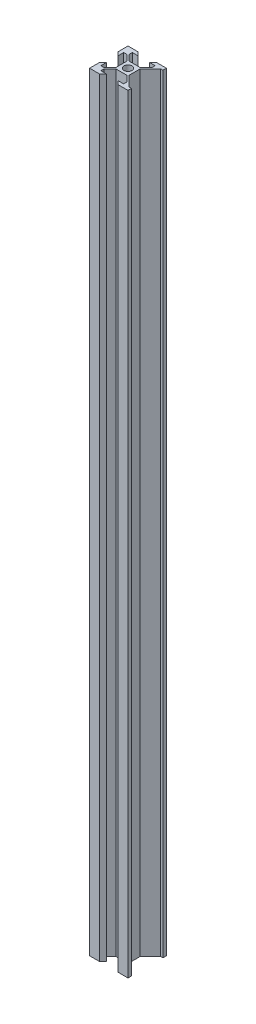
SolidWorks part; units mm, degrees
ref_plane "前视基准面" through (0, 0, 0) normal (0, 0, 1) x (1, 0, 0)
ref_plane "上视基准面" through (0, 0, 0) normal (0, 1, 0) x (1, 0, 0)
ref_plane "右视基准面" through (0, 0, 0) normal (1, 0, 0) x (0, 0, -1)
sketch "草图1" plane through (0, 0, 0) normal (0, 1, 0) x (1, 0, 0)
  line L0 (-25.721, 0) -> (73.7722, 0)
  line L1 (0, 21.255) -> (0, -16.6235)
  line L2 (-10, 21.255) -> (-10, -16.6235)
  line L3 (-25.721, 10) -> (73.7722, 10)
  line L4 (-4.9, 10) -> (-3.1, 8.2)
  line L5 (-3.1, 8.2) -> (-5.9236, 8.2)
  line L6 (-5.9236, 8.2) -> (-5.9236, 6.56)
  line L7 (-5.9236, 6.56) -> (-2.84, 3.4764)
  line L8 (-2.84, 3.4764) -> (2.84, 3.4764)
  line L9 (-10, 10) -> (0, 0) construction
  line L10 (5.9236, 6.56) -> (2.84, 3.4764)
  line L11 (5.9236, 8.2) -> (5.9236, 6.56)
  line L12 (3.1, 8.2) -> (5.9236, 8.2)
  line L13 (4.9, 10) -> (3.1, 8.2)
  line L14 (-10, -4.9) -> (-8.2, -3.1)
  line L15 (-8.2, -3.1) -> (-8.2, -5.9236)
  line L16 (-8.2, -5.9236) -> (-6.56, -5.9236)
  line L17 (-6.56, -5.9236) -> (-3.4764, -2.84)
  line L18 (-3.4764, 2.84) -> (-3.4764, -2.84)
  line L19 (-6.56, 5.9236) -> (-3.4764, 2.84)
  line L20 (-8.2, 5.9236) -> (-6.56, 5.9236)
  line L21 (-8.2, 3.1) -> (-8.2, 5.9236)
  line L22 (-10, 4.9) -> (-8.2, 3.1)
  line L23 (-25.721, -10) -> (73.7722, -10)
  line L24 (4.9, -10) -> (3.1, -8.2)
  line L25 (3.1, -8.2) -> (5.9236, -8.2)
  line L26 (5.9236, -8.2) -> (5.9236, -6.56)
  line L27 (5.9236, -6.56) -> (2.84, -3.4764)
  line L28 (-2.84, -3.4764) -> (2.84, -3.4764)
  line L29 (-5.9236, -6.56) -> (-2.84, -3.4764)
  line L30 (-5.9236, -8.2) -> (-5.9236, -6.56)
  line L31 (-3.1, -8.2) -> (-5.9236, -8.2)
  line L32 (-4.9, -10) -> (-3.1, -8.2)
  line L33 (50, 21.255) -> (50, -16.6235)
  line L34 (20, 21.255) -> (20, -16.6235)
  line L35 (10, 4.9) -> (8.2, 3.1)
  line L36 (8.2, 3.1) -> (8.2, 5.9236)
  line L37 (8.2, 5.9236) -> (6.56, 5.9236)
  line L38 (6.56, 5.9236) -> (3.4764, 2.84)
  line L39 (3.4764, 2.84) -> (3.4764, -2.84)
  line L40 (6.56, -5.9236) -> (3.4764, -2.84)
  line L41 (8.2, -5.9236) -> (6.56, -5.9236)
  line L42 (8.2, -3.1) -> (8.2, -5.9236)
  line L43 (10, -4.9) -> (8.2, -3.1)
  line L44 (15.1, 10) -> (16.9, 8.2)
  line L45 (16.9, 8.2) -> (14.0764, 8.2)
  line L46 (14.0764, 8.2) -> (14.0764, 6.56)
  line L47 (14.0764, 6.56) -> (17.16, 3.4764)
  line L48 (17.16, 3.4764) -> (22.84, 3.4764)
  line L49 (25.9236, 6.56) -> (22.84, 3.4764)
  line L50 (25.9236, 8.2) -> (25.9236, 6.56)
  line L51 (23.1, 8.2) -> (25.9236, 8.2)
  line L52 (24.9, 10) -> (23.1, 8.2)
  line L53 (10, -4.9) -> (11.8, -3.1)
  line L54 (11.8, -3.1) -> (11.8, -5.9236)
  line L55 (11.8, -5.9236) -> (13.44, -5.9236)
  line L56 (13.44, -5.9236) -> (16.5236, -2.84)
  line L57 (16.5236, 2.84) -> (16.5236, -2.84)
  line L58 (13.44, 5.9236) -> (16.5236, 2.84)
  line L59 (11.8, 5.9236) -> (13.44, 5.9236)
  line L60 (11.8, 3.1) -> (11.8, 5.9236)
  line L61 (10, 4.9) -> (11.8, 3.1)
  line L62 (24.9, -10) -> (23.1, -8.2)
  line L63 (23.1, -8.2) -> (25.9236, -8.2)
  line L64 (25.9236, -8.2) -> (25.9236, -6.56)
  line L65 (25.9236, -6.56) -> (22.84, -3.4764)
  line L66 (17.16, -3.4764) -> (22.84, -3.4764)
  line L67 (14.0764, -6.56) -> (17.16, -3.4764)
  line L68 (14.0764, -8.2) -> (14.0764, -6.56)
  line L69 (16.9, -8.2) -> (14.0764, -8.2)
  line L70 (15.1, -10) -> (16.9, -8.2)
  line L71 (30, 4.9) -> (28.2, 3.1)
  line L72 (28.2, 3.1) -> (28.2, 5.9236)
  line L73 (28.2, 5.9236) -> (26.56, 5.9236)
  line L74 (26.56, 5.9236) -> (23.4764, 2.84)
  line L75 (23.4764, 2.84) -> (23.4764, -2.84)
  line L76 (26.56, -5.9236) -> (23.4764, -2.84)
  line L77 (28.2, -5.9236) -> (26.56, -5.9236)
  line L78 (28.2, -3.1) -> (28.2, -5.9236)
  line L79 (30, -4.9) -> (28.2, -3.1)
  line L80 (6.56, 5.9236) -> (8.8364, 8.2)
  line L81 (35.1, 10) -> (36.9, 8.2)
  line L82 (36.9, 8.2) -> (34.0764, 8.2)
  line L83 (34.0764, 8.2) -> (34.0764, 6.56)
  line L84 (34.0764, 6.56) -> (37.16, 3.4764)
  line L85 (37.16, 3.4764) -> (42.84, 3.4764)
  line L86 (45.9236, 6.56) -> (42.84, 3.4764)
  line L87 (45.9236, 8.2) -> (45.9236, 6.56)
  line L88 (43.1, 8.2) -> (45.9236, 8.2)
  line L89 (44.9, 10) -> (43.1, 8.2)
  line L90 (30, -4.9) -> (31.8, -3.1)
  line L91 (31.8, -3.1) -> (31.8, -5.9236)
  line L92 (31.8, -5.9236) -> (33.44, -5.9236)
  line L93 (33.44, -5.9236) -> (36.5236, -2.84)
  line L94 (36.5236, 2.84) -> (36.5236, -2.84)
  line L95 (33.44, 5.9236) -> (36.5236, 2.84)
  line L96 (31.8, 5.9236) -> (33.44, 5.9236)
  line L97 (31.8, 3.1) -> (31.8, 5.9236)
  line L98 (30, 4.9) -> (31.8, 3.1)
  line L99 (44.9, -10) -> (43.1, -8.2)
  line L100 (43.1, -8.2) -> (45.9236, -8.2)
  line L101 (45.9236, -8.2) -> (45.9236, -6.56)
  line L102 (45.9236, -6.56) -> (42.84, -3.4764)
  line L103 (37.16, -3.4764) -> (42.84, -3.4764)
  line L104 (34.0764, -6.56) -> (37.16, -3.4764)
  line L105 (34.0764, -8.2) -> (34.0764, -6.56)
  line L106 (36.9, -8.2) -> (34.0764, -8.2)
  line L107 (35.1, -10) -> (36.9, -8.2)
  line L108 (50, 4.9) -> (48.2, 3.1)
  line L109 (48.2, 3.1) -> (48.2, 5.9236)
  line L110 (48.2, 5.9236) -> (46.56, 5.9236)
  line L111 (46.56, 5.9236) -> (43.4764, 2.84)
  line L112 (43.4764, 2.84) -> (43.4764, -2.84)
  line L113 (46.56, -5.9236) -> (43.4764, -2.84)
  line L114 (48.2, -5.9236) -> (46.56, -5.9236)
  line L115 (48.2, -3.1) -> (48.2, -5.9236)
  line L116 (50, -4.9) -> (48.2, -3.1)
  line L117 (13.44, 5.9236) -> (11.1636, 8.2)
  line L118 (30, 10) -> (40, 0) construction
  line L119 (10, 10) -> (20, 0) construction
  line L120 (8.8364, 8.2) -> (11.1636, 8.2)
  line L121 (8.8364, -8.2) -> (11.1636, -8.2)
  line L122 (6.56, -5.9236) -> (8.8364, -8.2)
  line L123 (13.44, -5.9236) -> (11.1636, -8.2)
  line L124 (26.56, 5.9236) -> (28.8364, 8.2)
  line L125 (28.8364, 8.2) -> (31.1636, 8.2)
  line L126 (33.44, 5.9236) -> (31.1636, 8.2)
  line L127 (26.56, -5.9236) -> (28.8364, -8.2)
  line L128 (28.8364, -8.2) -> (31.1636, -8.2)
  line L129 (33.44, -5.9236) -> (31.1636, -8.2)
  circle A0 centre (0, 0) radius 2.1
  circle A1 centre (20, 0) radius 2.1
  circle A2 centre (40, 0) radius 2.1
  circle A3 centre (20, 0) radius 2.1
  circle A4 centre (40, 0) radius 2.1
  point P22 (0, 3.4764)
  point P37 (-3.4764, 0)
  point P50 (0, -3.4764)
  point P65 (3.4764, 0)
  point P77 (20, 3.4764)
  point P92 (16.5236, 0)
  point P103 (20, -3.4764)
  point P114 (23.4764, 0)
  point P124 (40, 3.4764)
  point P139 (36.5236, 0)
  point P150 (40, -3.4764)
  point P161 (43.4764, 0)
  dimension "D1" = 3
  dimension "D2" = 4.2
  dimension "D3" = 20
  dimension "D6" = 1.8
  dimension "D7" = 1.64
  dimension "D8" = 2.84
  dimension "D9" = 3.1
  dimension "D10" = 45
  dimension "D11" = 0.9
  dimension "D16" = 2
  dimension "D4" = 10
  dimension "D5" = 10
  dimension "D12" = 10
  dimension "D13" = 60
  dimension "D14" = 30
  dimension "D15" = 3
extrude "凸台-拉伸1" add sketch "草图1" along normal blind 400 contours A0 L1 L8 L7 L6 L5 L4 L3 L2 L22 L21 L20 L19 L18 L0 | A0 L0 L18 L17 L16 L15 L14 L2 L23 L32 L31 L30 L29 L28 L1 | A1 L0 L57 L56 L123 L121 L122 L40 L39 A0 L1 L28 L27 L26 L25 L24 L23 L70 L69 L68 L67 L66 L34 | A1 L34 L48 L47 L46 L45 L44 L3 L13 L12 L11 L10 L8 L1 A0 L0 L39 L38 L80 L120 L117 L58 L57 | A2 L0 L112 L111 L110 L109 L108 L33 L3 L89 L88 L87 L86 L85 L84 L83 L82 L81 L52 L51 L50 L49 L48 L34 A1 L75 L74 L124 L125 L126 L95 L94 | A2 L0 L94 L93 L129 L128 L127 L76 L75 A1 L34 L66 L65 L64 L63 L62 L23 L107 L106 L105 L104 L103 L102 L101 L100 L99 L33 L116 L115 L114 L113 L112
sketch "草图2" plane through (0, 400, 0) normal (0, 1, 0) x (1, 0, 0)
  line L0 (4.9, 10) -> (15.1, 10) construction
  line L1 (10, 10) -> (54.3529, 10)
  line L2 (10, 10) -> (10, -16.4474)
  line L3 (10, -16.4474) -> (54.3529, -16.4474)
  line L4 (54.3529, 10) -> (54.3529, -16.4474)
extrude "切除-拉伸1" cut sketch "草图2" against normal through all both and the other way through all
